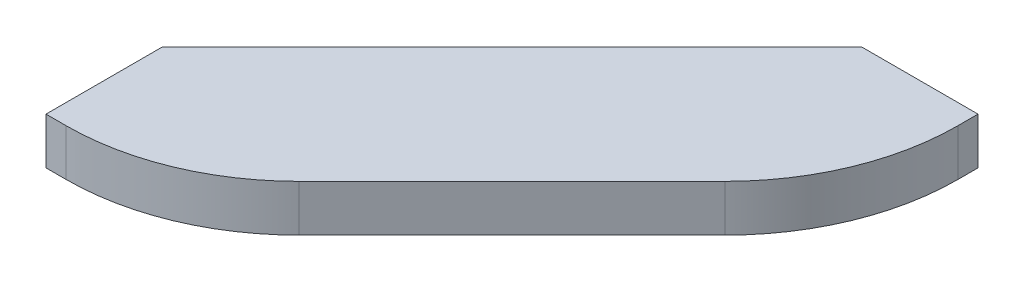
SolidWorks part; units mm, degrees
ref_plane "Front Plane" through (0, 0, 0) normal (0, 0, 1) x (1, 0, 0)
ref_plane "Top Plane" through (0, 0, 0) normal (0, 1, 0) x (1, 0, 0)
ref_plane "Right Plane" through (0, 0, 0) normal (1, 0, 0) x (0, 0, -1)
sketch "Sketch1" plane through (0, 0, 0) normal (0, 1, 0) x (1, 0, 0)
  line L1 (-25.4, -25.4) -> (25.4, -25.4)
  line L2 (-25.4, -25.4) -> (-25.4, 25.4)
  line L3 (-25.4, 25.4) -> (25.4, 25.4)
  line L4 (25.4, -25.4) -> (25.4, 25.4)
  line L5 (-25.4, -25.4) -> (25.4, 25.4) construction
  line L6 (-25.4, 25.4) -> (25.4, -25.4) construction
  point P0 (0, 0)
  dimension "D1" = 50.8
  dimension "D2" = 50.8
extrude "Boss-Extrude1" add sketch "Sketch1" along normal blind 5.08
sketch "Sketch6" plane through (0, 5.08, 0) normal (0, 1, 0) x (1, 0, 0)
  line L0 (-25.4, -25.4) -> (-25.4, -12.7) construction
  line L1 (-25.4, 25.4) -> (-25.4, -25.4) construction
  line L2 (-25.4, -12.7) -> (-25.4, 25.4)
  line L3 (-25.4, 25.4) -> (12.7, 25.4)
  line L4 (25.4, 25.4) -> (-25.4, 25.4) construction
  line L5 (12.7, 25.4) -> (25.4, 25.4) construction
  line L6 (25.4, 25.4) -> (25.4, 12.7) construction
  line L7 (25.4, -25.4) -> (25.4, 25.4) construction
  line L8 (25.4, 12.7) -> (25.4, -25.4)
  line L9 (-25.4, -25.4) -> (25.4, -25.4) construction
  line L10 (25.4, -25.4) -> (-12.7, -25.4)
  line L11 (-12.7, -25.4) -> (-25.4, -25.4) construction
  line L12 (-25.4, -12.7) -> (12.7, 25.4)
  line L13 (25.4, 12.7) -> (-12.7, -25.4)
  dimension "D1" = 12.7
extrude "Cut-Extrude1" cut sketch "Sketch6" against normal blind 50.8
fillet "Fillet1" radius 25.4 2 edges at (25.4, 2.54, -12.7) (-12.7, 2.54, 25.4)
equation "\"Foamcore\" = .1in"
equation "\"MDF\" = .2in"
equation "\"Gmaterial\"= \"MDF\""
equation "\"PVC-ID\" = \"1.590in\""
equation "\"PVC-OD\" = \"1.900in\""
equation "\"D1@Boss-Extrude1\"=\"Gmaterial\""
